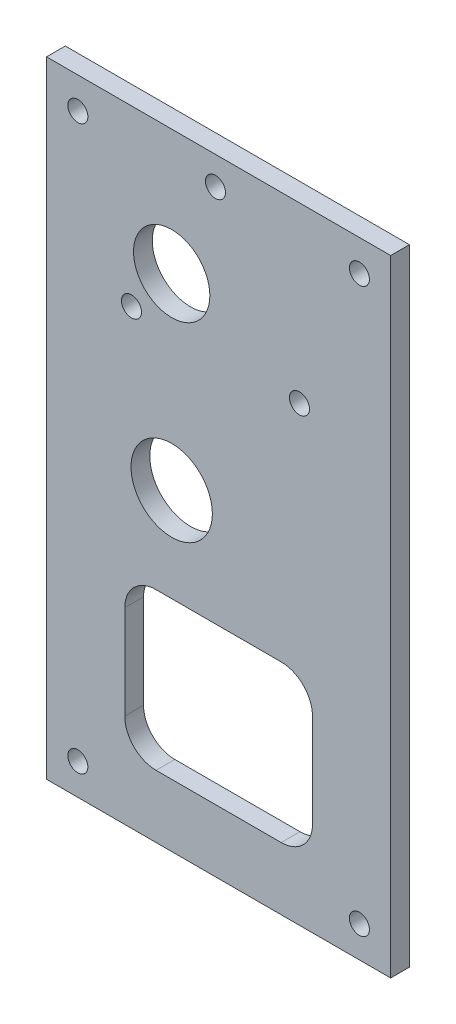
SolidWorks part; units mm, degrees
material "5052-O"
ref_plane "正面" through (0, 0, 0) normal (0, 0, 1) x (1, 0, 0)
ref_plane "平面" through (0, 0, 0) normal (0, 1, 0) x (1, 0, 0)
ref_plane "右側面" through (0, 0, 0) normal (1, 0, 0) x (0, 0, -1)
sketch "ｽｹｯﾁ1" plane through (0, 0, 0) normal (0, 0, 1) x (1, 0, 0)
  line L1 (-27.5, 50) -> (27.5, 50)
  line L2 (-27.5, 50) -> (-27.5, -50)
  line L3 (-27.5, -50) -> (27.5, -50)
  line L4 (27.5, 50) -> (27.5, -50)
  line L5 (-27.5, 50) -> (27.5, -50) construction
  line L6 (-27.5, -50) -> (27.5, 50) construction
  point P0 (0, 0)
  dimension "D1" = 55
  dimension "D2" = 100
extrude "ﾎﾞｽ - 押し出し1" add sketch "ｽｹｯﾁ1" along normal mid plane 3
sketch "ｽｹｯﾁ2" plane through (0, 0, 1.5) normal (0, 0, 1) x (1, 0, 0)
  line L0 (27.5, -50) -> (27.5, 50) construction
  circle A0 centre (-7.5, 30) radius 6.1
  circle A2 centre (6.5, 30) radius 6.1
  circle A3 centre (-0.5, 30) radius 15.5
  circle A4 centre (-0.5, 14.5) radius 1.6
  circle A5 centre (-13.9234, 22.25) radius 1.6
  circle A6 centre (-13.9234, 37.75) radius 1.6
  circle A7 centre (-0.5, 45.5) radius 1.6
  circle A8 centre (12.9234, 37.75) radius 1.6
  circle A9 centre (12.9234, 22.25) radius 1.6
  circle A10 centre (-7.5, 0) radius 6.5
  point P22 (-0.5, 30)
  dimension "D1" = 12.2
  dimension "D2" = 2
  dimension "D3" = 31
  dimension "D6" = 3.2
  dimension "D7" = 0
  dimension "D9" = 30
  dimension "D10" = 13
  dimension "D11" = 35
  dimension "D4" = 0
  dimension "D5" = 7
  dimension "D12" = 0
  dimension "D13" = 0
  dimension "D8" = 6
extrude "ｶｯﾄ - 押し出し1" cut sketch "ｽｹｯﾁ2" against normal through all contours A0 | A10 | A9 | A7 | A5
sketch "ｽｹｯﾁ3" plane through (0, 0, 1.5) normal (0, 0, 1) x (1, 0, 0)
  line L0 (27.5, 50) -> (-27.5, 50) construction
  line L1 (-27.5, 50) -> (-27.5, -50) construction
  line L2 (0, -1.65) -> (0, 1.65) construction
  line L3 (1.65, 0) -> (-1.65, 0) construction
  circle A0 centre (-22.5, 45) radius 1.6
  circle A1 centre (22.5, 45) radius 1.6
  circle A2 centre (22.5, -45) radius 1.6
  circle A3 centre (-22.5, -45) radius 1.6
  dimension "D1" = 3.2
  dimension "D2" = 5
  dimension "D3" = 5
extrude "ｶｯﾄ - 押し出し2" cut sketch "ｽｹｯﾁ3" against normal through all
sketch "ｽｹｯﾁ4" plane through (0, 0, 1.5) normal (0, 0, 1) x (1, 0, 0)
  line L0 (-27.5, -50) -> (27.5, -50) construction
  line L1 (-15, -15) -> (15, -15)
  line L2 (-15, -15) -> (-15, -40)
  line L3 (-15, -40) -> (15, -40)
  line L4 (15, -15) -> (15, -40)
  line L5 (-15, -15) -> (15, -40) construction
  line L6 (-15, -40) -> (15, -15) construction
  point P0 (0, -27.5)
  dimension "D1" = 30
  dimension "D2" = 0
  dimension "D3" = 25
  dimension "D4" = 10
extrude "ｶｯﾄ - 押し出し3" cut sketch "ｽｹｯﾁ4" against normal through all
fillet "ﾌｨﾚｯﾄ1" radius 5 4 edges at (15, -40, 0) (-15, -40, 0) (15, -15, 0) (-15, -15, 0)
